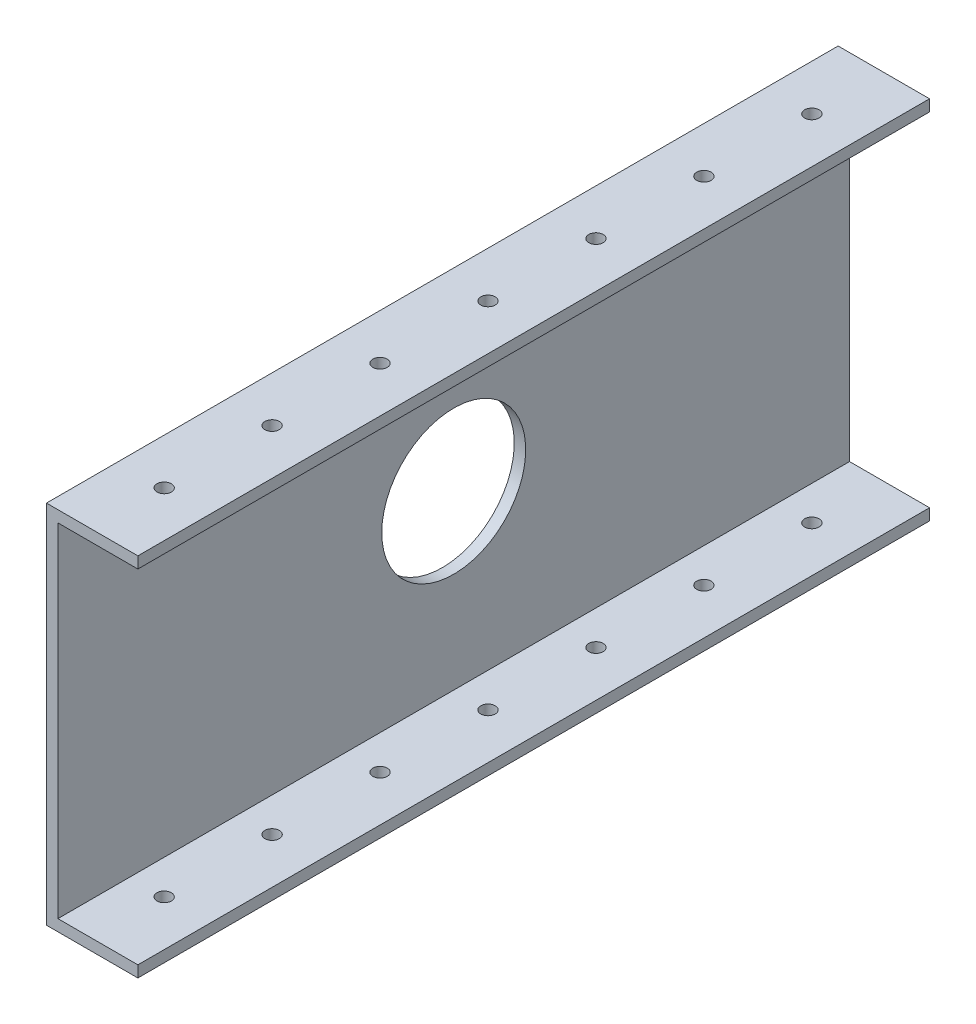
SolidWorks part; units mm, degrees
ref_plane "Front Plane" through (0, 0, 0) normal (0, 0, 1) x (1, 0, 0)
ref_plane "Top Plane" through (0, 0, 0) normal (0, 1, 0) x (1, 0, 0)
ref_plane "Right Plane" through (0, 0, 0) normal (1, 0, 0) x (0, 0, -1)
sketch "Sketch1" plane through (0, 0, 0) normal (0, 0, 1) x (1, 0, 0)
  line L0 (0, -51.0466) -> (0, 50.5534)
  line L1 (0, 50.5534) -> (25.4, 50.5534)
  line L2 (0, -51.0466) -> (25.4, -51.0466)
  line L3 (3.175, -47.8716) -> (25.4, -47.8716)
  line L4 (3.175, -47.8716) -> (3.175, 47.3784)
  line L5 (3.175, 47.3784) -> (25.4, 47.3784)
  line L6 (25.4, 50.5534) -> (25.4, 47.3784)
  line L7 (25.4, -47.8716) -> (25.4, -51.0466)
  dimension "D1" = 101.6
  dimension "D2" = 25.4
  dimension "D3" = 25.4
  dimension "D4" = 3.175
extrude "Boss-Extrude1" add sketch "Sketch1" along normal blind 220
sketch "Sketch2" plane through (0, 50.5534, 0) normal (0, 1, 0) x (1, 0, 0)
  line L0 (12.7, 0) -> (12.7, -220) construction
  line L1 (25.4, 0) -> (0, 0) construction
  line L2 (25.4, -220) -> (0, -220) construction
  circle A0 centre (12.7, -110) radius 2
  circle A1 centre (12.7, -80) radius 2
  circle A2 centre (12.7, -50) radius 2
  circle A3 centre (12.7, -20) radius 2
  circle A4 centre (12.7, -140) radius 2
  circle A5 centre (12.7, -170) radius 2
  circle A6 centre (12.7, -200) radius 2
  dimension "D1" = 4
  dimension "D2" = 4
extrude "Cut-Extrude1" cut sketch "Sketch2" against normal up to surface (101.6 mm away) up to face at (12.7, -51.0466, 110)
sketch "Sketch3" plane through (0, 0, 0) normal (-1, 0, 0) x (0, 0, 1)
  circle A0 centre (110, 0) radius 20
  dimension "D1" = 40
extrude "Cut-Extrude2" cut sketch "Sketch3" against normal blind 220
